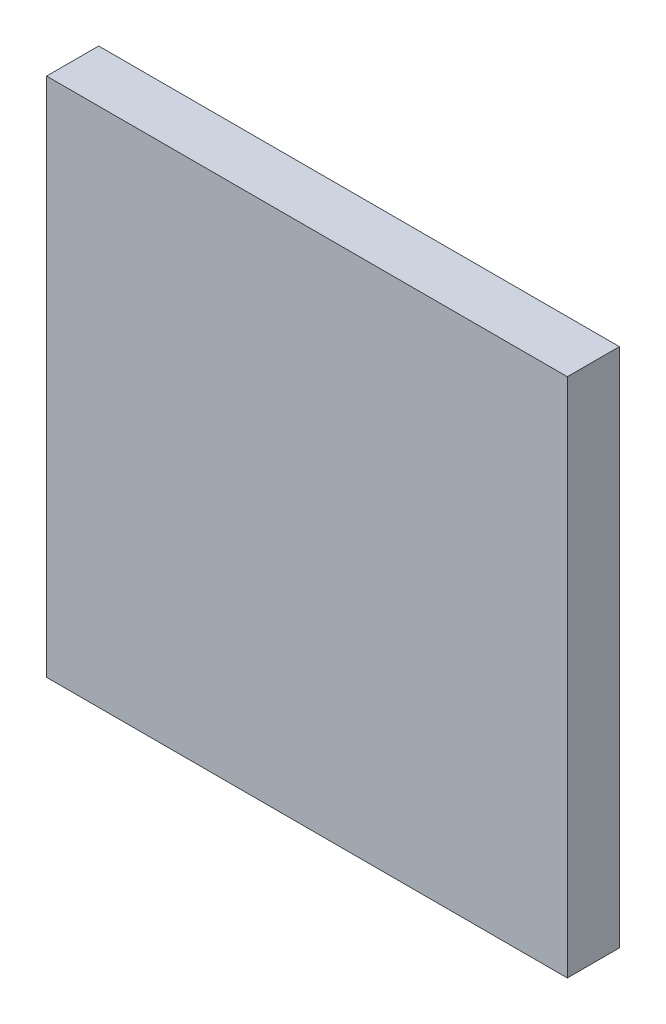
SolidWorks part; units mm, degrees
ref_plane "Front Plane" through (0, 0, 0) normal (0, 0, 1) x (1, 0, 0)
ref_plane "Top Plane" through (0, 0, 0) normal (0, 1, 0) x (1, 0, 0)
ref_plane "Right Plane" through (0, 0, 0) normal (1, 0, 0) x (0, 0, -1)
sketch "Sketch1" plane through (0, 0, 0) normal (0, 0, 1) x (1, 0, 0)
  line L1 (0, 0) -> (1000, 0)
  line L2 (0, 0) -> (0, 1000)
  line L3 (0, 1000) -> (1000, 1000)
  line L4 (1000, 0) -> (1000, 1000)
  dimension "D1" = 1000
  dimension "D2" = 1000
extrude "Boss-Extrude1" add sketch "Sketch1" along normal blind 100
sketch "Sketch2" plane through (0, 0, 0) normal (0, -1, 0) x (1, 0, 0)
  line L0 (100, 100) -> (100, 0)
  line L1 (0, 100) -> (1000, 100) construction
  line L2 (0, 0) -> (1000, 0) construction
  line L3 (250, 100) -> (250, 0)
  line L4 (350, 100) -> (350, 0)
  line L5 (900, 100) -> (900, 0)
  line L6 (0, 100) -> (0, 0) construction
  line L7 (1000, 100) -> (1000, 0) construction
  dimension "D1" = 100
  dimension "D2" = 100
  dimension "D3" = 100
  dimension "D4" = 250
split line "Split Line1"
